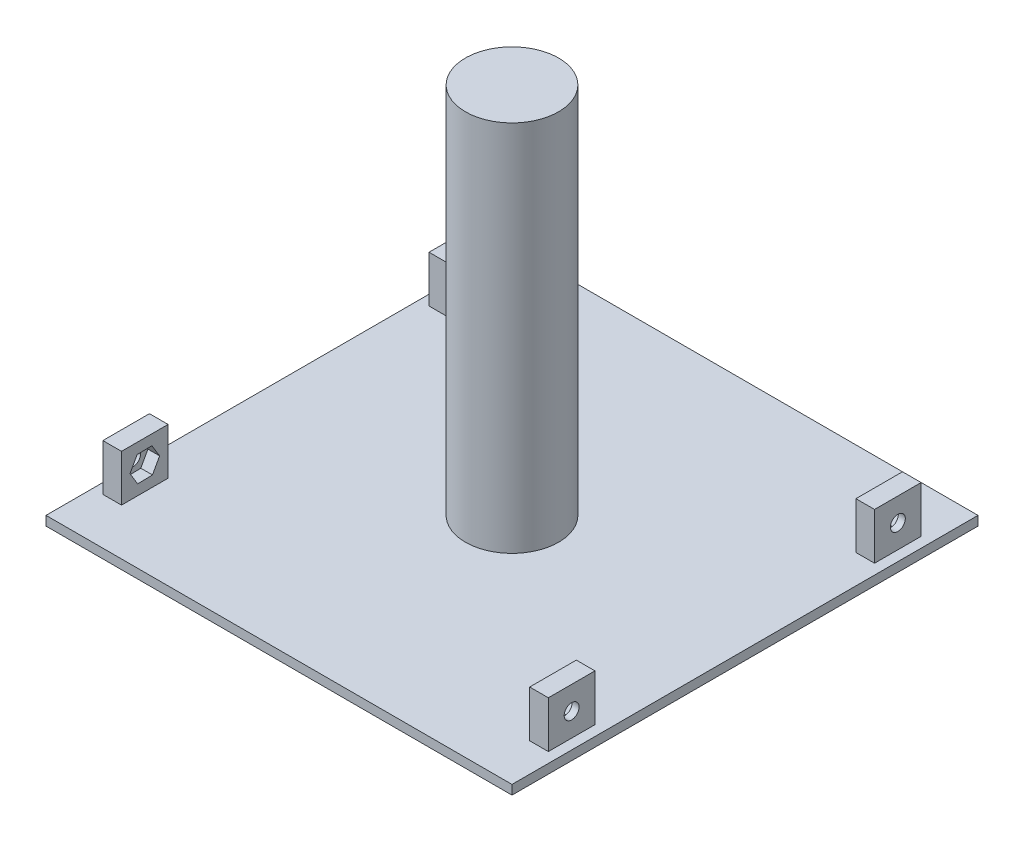
SolidWorks part; units mm, degrees
ref_plane "Ön Düzlem" through (0, 0, 0) normal (0, 0, 1) x (1, 0, 0)
ref_plane "Üst Düzlem" through (0, 0, 0) normal (0, 1, 0) x (1, 0, 0)
ref_plane "Sağ Düzlem" through (0, 0, 0) normal (1, 0, 0) x (0, 0, -1)
sketch "Çizim1" plane through (0, 0, 0) normal (0, 1, 0) x (1, 0, 0)
  line L1 (-50, 50) -> (50, 50)
  line L2 (-50, 50) -> (-50, -50)
  line L3 (-50, -50) -> (50, -50)
  line L4 (50, 50) -> (50, -50)
  line L5 (-50, 50) -> (50, -50) construction
  line L6 (-50, -50) -> (50, 50) construction
  point P0 (0, 0)
  dimension "D1" = 100
  dimension "D2" = 100
extrude "Yükseklik-Ekstrüzyon1" add sketch "Çizim1" along normal blind 2
sketch "Çizim2" plane through (0, 2, 0) normal (0, 1, 0) x (1, 0, 0)
  circle A0 centre (0, 0) radius 10
extrude "Yükseklik-Ekstrüzyon2" add sketch "Çizim2" along normal blind 80
sketch "Çizim3" plane through (0, 2, 0) normal (0, 1, 0) x (1, 0, 0)
  line L0 (-50, 50) -> (-50, -50) construction
  line L1 (-47.8, 40) -> (-43.8, 40)
  line L2 (-47.8, 40) -> (-47.8, 30)
  line L3 (-47.8, 30) -> (-43.8, 30)
  line L4 (-43.8, 40) -> (-43.8, 30)
  line L5 (43.8, 40) -> (43.8, 30)
  line L6 (43.8, 40) -> (47.8, 40)
  line L7 (47.8, 40) -> (47.8, 30)
  line L8 (43.8, 30) -> (47.8, 30)
  line L9 (50, -50) -> (50, 50) construction
  line L10 (-47.8, -30) -> (-47.8, -40)
  line L11 (-47.8, -30) -> (-43.8, -30)
  line L12 (-43.8, -30) -> (-43.8, -40)
  line L13 (-47.8, -40) -> (-43.8, -40)
  line L14 (43.8, -30) -> (43.8, -40)
  line L15 (43.8, -40) -> (47.8, -40)
  line L16 (47.8, -30) -> (47.8, -40)
  line L17 (43.8, -30) -> (47.8, -30)
  line L18 (50, 50) -> (-50, 50) construction
  line L19 (-50, -50) -> (50, -50) construction
  dimension "D1" = 4
  dimension "D2" = 10
  dimension "D3" = 2.2
  dimension "D5" = 2.2
  dimension "D7" = 10
  dimension "D8" = 10
  dimension "D4" = 2
  dimension "D6" = 2
extrude "Yükseklik-Ekstrüzyon3" add sketch "Çizim3" along normal blind 10
sketch "Çizim5" plane through (-43.8, 0, 0) normal (1, 0, 0) x (0, 0, -1)
  line L0 (-30, 2) -> (-40, 12) construction
  line L1 (-30, 12) -> (-40, 2) construction
  line L2 (40, 2) -> (30, 12) construction
  line L3 (-36.5261, 4.2154) -> (-33.3515, 4.286)
  line L4 (-33.3515, 4.286) -> (-31.8254, 7.0706)
  line L5 (-31.8254, 7.0706) -> (-33.4739, 9.7846)
  line L6 (-33.4739, 9.7846) -> (-36.6485, 9.714)
  line L7 (-36.6485, 9.714) -> (-38.1746, 6.9294)
  line L8 (-38.1746, 6.9294) -> (-36.5261, 4.2154)
  line L9 (40, 12) -> (30, 2) construction
  line L10 (33.4739, 4.2154) -> (36.6485, 4.286)
  line L11 (36.6485, 4.286) -> (38.1746, 7.0706)
  line L12 (38.1746, 7.0706) -> (36.5261, 9.7846)
  line L13 (36.5261, 9.7846) -> (33.3515, 9.714)
  line L14 (33.3515, 9.714) -> (31.8254, 6.9294)
  line L15 (31.8254, 6.9294) -> (33.4739, 4.2154)
  circle A0 centre (-35, 7) radius 2.75 construction
  dimension "D1" = 5.5
  dimension "D2" = 2
extrude "Kes-Ekstrüzyon1" cut sketch "Çizim5" against normal blind 2.5
sketch "Çizim6" plane through (-43.8, 0, 0) normal (1, 0, 0) x (0, 0, -1)
  line L0 (-30, 12) -> (-40, 2) construction
  line L1 (-40, 12) -> (-30, 2) construction
  circle A0 centre (-35, 7) radius 1.6
  circle A1 centre (35, 7) radius 1.6
  dimension "D1" = 2
extrude "Kes-Ekstrüzyon2" cut sketch "Çizim6" against normal blind 5
sketch "Çizim7" plane through (43.8, 0, 0) normal (-1, 0, 0) x (0, 0, 1)
  line L0 (30, 12) -> (40, 2) construction
  line L1 (30, 2) -> (40, 12) construction
  line L2 (-33.4757, 9.7857) -> (-36.6503, 9.7129)
  line L3 (36.5243, 9.7857) -> (33.3497, 9.7129)
  line L4 (33.3497, 9.7129) -> (31.8254, 6.9272)
  line L5 (31.8254, 6.9272) -> (33.4757, 4.2143)
  line L6 (33.4757, 4.2143) -> (36.6503, 4.2871)
  line L7 (36.6503, 4.2871) -> (38.1746, 7.0728)
  line L8 (38.1746, 7.0728) -> (36.5243, 9.7857)
  line L9 (-36.6503, 9.7129) -> (-38.1746, 6.9272)
  line L10 (-38.1746, 6.9272) -> (-36.5243, 4.2143)
  line L11 (-36.5243, 4.2143) -> (-33.3497, 4.2871)
  line L12 (-33.3497, 4.2871) -> (-31.8254, 7.0728)
  line L13 (-31.8254, 7.0728) -> (-33.4757, 9.7857)
  circle A0 centre (35, 7) radius 2.75 construction
  point P9 (34.937, 9.7493)
  dimension "D1" = 5.5
  dimension "D2" = 2
extrude "Kes-Ekstrüzyon3" cut sketch "Çizim7" against normal blind 2.5
sketch "Çizim8" plane through (43.8, 0, 0) normal (-1, 0, 0) x (0, 0, 1)
  line L0 (30, 12) -> (40, 2) construction
  line L1 (30, 2) -> (40, 12) construction
  circle A0 centre (35, 7) radius 1.6
  circle A1 centre (-35, 7) radius 1.6
  dimension "D1" = 2
extrude "Kes-Ekstrüzyon4" cut sketch "Çizim8" against normal blind 5
